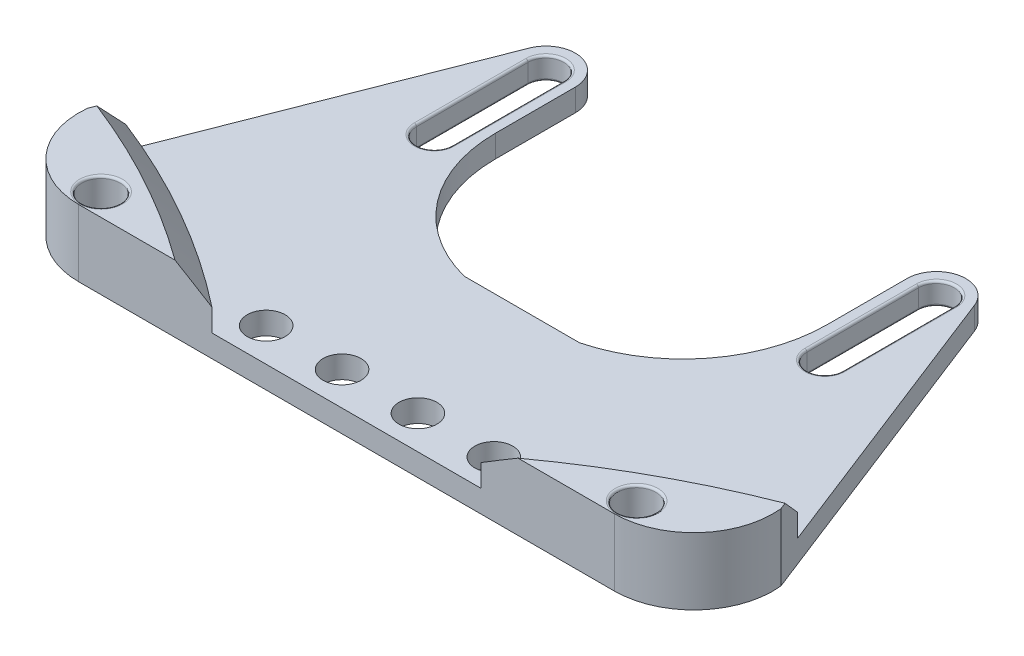
SolidWorks part; units mm, degrees
ref_plane "Plano frontal" through (0, 0, 0) normal (0, 0, 1) x (1, 0, 0)
ref_plane "Plano superior" through (0, 0, 0) normal (0, 1, 0) x (1, 0, 0)
ref_plane "Plano direito" through (0, 0, 0) normal (1, 0, 0) x (0, 0, -1)
sketch "Esboço1" plane through (0, 0, 0) normal (0, 1, 0) x (1, 0, 0)
  line L0 (0, 0) -> (0, 32.3533) construction
  line L1 (0, 0) -> (0, -30.7316) construction
  line L2 (-24, -20.3729) -> (24, -20.3729)
  line L3 (30.9923, 0) -> (-41.1659, 0) construction
  line L4 (-5.1651, -4.6606) -> (5.1651, -4.6606)
  line L5 (-19.9572, 15.9596) -> (-31.0775, -12.5175)
  line L6 (14.8621, 15) -> (14.8621, 7.8455)
  line L7 (19.9572, 15.9596) -> (31.0775, -12.5175)
  line L8 (-14.8621, 15) -> (-14.8621, 7.8455)
  line L9 (-17.5, 15) -> (-17.5, 5) construction
  line L10 (-15.9, 15) -> (-15.9, 5)
  line L11 (-19.1, 15) -> (-19.1, 5)
  line L12 (17.5, 15) -> (17.5, 5) construction
  line L13 (15.9, 15) -> (15.9, 5)
  line L14 (19.1, 15) -> (19.1, 5)
  arc A0 (-15.9, 15) -> (-19.1, 15) centre (-17.5, 15) ccw
  arc A1 (-24, -20.3729) -> (-31.0775, -12.5175) centre (-24, -13.2569) cw
  arc A2 (-14.8621, 15) -> (-19.9572, 15.9596) centre (-17.5, 15) ccw
  arc A3 (-14.8621, 7.8455) -> (-5.1651, -4.6606) centre (-1.9491, 7.8455) ccw
  circle A4 centre (24, -18.3729) radius 1.725
  arc A5 (14.8621, 7.8455) -> (5.1651, -4.6606) centre (1.9491, 7.8455) cw
  arc A6 (14.8621, 15) -> (19.9572, 15.9596) centre (17.5, 15) cw
  arc A7 (24, -20.3729) -> (31.0775, -12.5175) centre (24, -13.2569) ccw
  arc A8 (15.9, 15) -> (19.1, 15) centre (17.5, 15) cw
  arc A9 (-19.1, 5) -> (-15.9, 5) centre (-17.5, 5) ccw
  circle A10 centre (-24, -18.3729) radius 1.725
  arc A11 (19.1, 5) -> (15.9, 5) centre (17.5, 5) cw
  point P4 (-17.5, 10)
  point P18 (0, -4.6606)
  point P19 (0, -20.3729)
  point P37 (17.5, 10)
  dimension "D3" = 2
  dimension "D6" = 24
  dimension "D12" = 7.1545
  dimension "D13" = 2.6379
  dimension "D10" = 30.5713
  dimension "D11" = 7.116
  dimension "D9" = 24
  dimension "D8" = 3.45
  dimension "D14" = 1.6
  dimension "D15" = 10
  dimension "D7" = 12.913
  dimension "D16" = 4.6606
  dimension "D2" = 17.5
  dimension "D4" = 5.1651
  dimension "D5" = 34
extrude "Ressalto-extrusão1" add sketch "Esboço1" along normal blind 2
sketch "Esboço2" plane through (0, 2, 0) normal (0, 1, 0) x (1, 0, 0)
  line L0 (0, 0) -> (0, -22.4652) construction
  line L1 (-12.06, -20.3729) -> (-24, -20.3729)
  line L3 (30.1118, -10.0445) -> (31.0775, -12.5175)
  line L4 (12.06, -20.3729) -> (24, -20.3729)
  line L5 (-19.9572, 15.9596) -> (-31.0775, -12.5175) construction
  line L6 (-30.1118, -10.0445) -> (-31.0775, -12.5175)
  line L7 (-24, -20.3729) -> (24, -20.3729) construction
  arc A0 (-24, -20.3729) -> (-31.0775, -12.5175) centre (-24, -13.2569) cw
  arc A2 (-30.1118, -10.0445) -> (-12.06, -20.3729) centre (-55.8668, -75.9983) cw
  circle A3 centre (-24, -18.3729) radius 1.725
  circle A4 centre (24, -18.3729) radius 1.725
  arc A5 (30.1118, -10.0445) -> (12.06, -20.3729) centre (55.8668, -75.9983) ccw
  arc A6 (24, -20.3729) -> (31.0775, -12.5175) centre (24, -13.2569) ccw
  dimension "D1" = 3.45
  dimension "D2" = 70.8041
  dimension "D3" = 70.3703
  dimension "D4" = 55.6254
extrude "Ressalto-extrusão2" add sketch "Esboço2" along normal blind 4
chamfer "Chanfro1" distance 2 angle 45 2 edges at (-20.7046, 6, 14.5423) (20.7046, 6, 14.5423)
sketch "Esboço3" plane through (0, 2, 0) normal (0, 1, 0) x (1, 0, 0)
  line L0 (0, -20.3729) -> (0, -11.6177) construction
  line L2 (-12.06, -20.3729) -> (12.06, -20.3729) construction
  line L3 (-12.06, -20.3729) -> (12.06, -20.3729) construction
  circle A0 centre (-3.4, -17.3729) radius 1.7
  circle A1 centre (-10.2, -17.3729) radius 1.7
  circle A2 centre (10.2, -17.3729) radius 1.7
  circle A3 centre (3.4, -17.3729) radius 1.7
  dimension "D1" = 3.4
  dimension "D2" = 3.4
  dimension "D3" = 3.4
  dimension "D4" = 3
  dimension "D5" = 6.8
  dimension "D6" = 3
extrude "Corte-extrusão1" cut sketch "Esboço3" against normal blind 4
fillet "Filete3" radius 0.2 20 edges at (17.5, 0, -3.4) (15.9, 0, -10) (17.5, 0, -16.6) (17.5, 2, -3.4) (15.9, 2, -10) (17.5, 2, -16.6) (-17.5, 0, -3.4) (-19.1, 0, -10) (-17.5, 0, -16.6) (-17.5, 2, -3.4) (-19.1, 2, -10) (-17.5, 2, -16.6) (24, 0, 16.6479) (24, 6, 16.6479) (-24, 0, 20.0979) (-24, 6, 20.0979) (19.1, 0, -10) (19.1, 2, -10) (-15.9, 0, -10) (-15.9, 2, -10)
